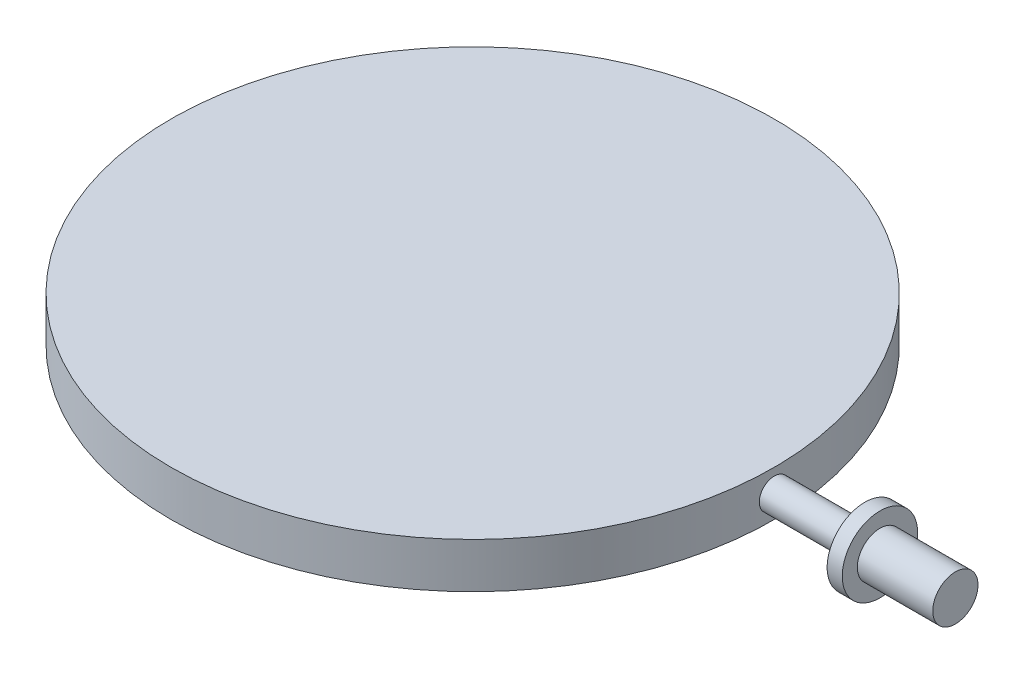
SolidWorks part; units mm, degrees
ref_plane "Front Plane" through (0, 0, 0) normal (0, 0, 1) x (1, 0, 0)
ref_plane "Top Plane" through (0, 0, 0) normal (0, 1, 0) x (1, 0, 0)
ref_plane "Right Plane" through (0, 0, 0) normal (1, 0, 0) x (0, 0, -1)
sketch "Sketch1" plane through (0, 0, 0) normal (0, 1, 0) x (1, 0, 0)
  circle A0 centre (0, 0) radius 100
  dimension "D1" = 200
extrude "Boss-Extrude1" add sketch "Sketch1" along normal blind 15
ref_plane "Plane1" through (100, 0, 0) normal (1, 0, 0) x (0, 0, -1)
sketch "Sketch2" plane through (100, 0, 0) normal (1, 0, 0) x (0, 0, -1)
  line L0 (100, 15) -> (-100, 15) construction
  circle A0 centre (0, 7.5) radius 5
  dimension "D1" = 10
  dimension "D2" = 7.5
  dimension "D3" = 7.5
extrude "Boss-Extrude2" add sketch "Sketch2" along normal blind 30 separate body
sketch "Sketch3" plane through (130, 0, 0) normal (1, 0, 0) x (0, 0, -1)
  circle A0 centre (0, 7.5) radius 12.5
  dimension "D1" = 25
extrude "Boss-Extrude3" add sketch "Sketch3" along normal blind 5
sketch "Sketch4" plane through (135, 0, 0) normal (1, 0, 0) x (0, 0, -1)
  circle A0 centre (0, 7.5) radius 7.5
  circle A1 centre (0, 7.5) radius 12.5 construction
  dimension "D1" = 15
  dimension "D2" = 0
extrude "Boss-Extrude4" add sketch "Sketch4" along normal blind 25
sketch "Sketch5" plane through (0, 15, 0) normal (0, 1, 0) x (1, 0, 0)
  text T0 "Aya " font "@Kozuka Gothic Pr6N M" height 10
